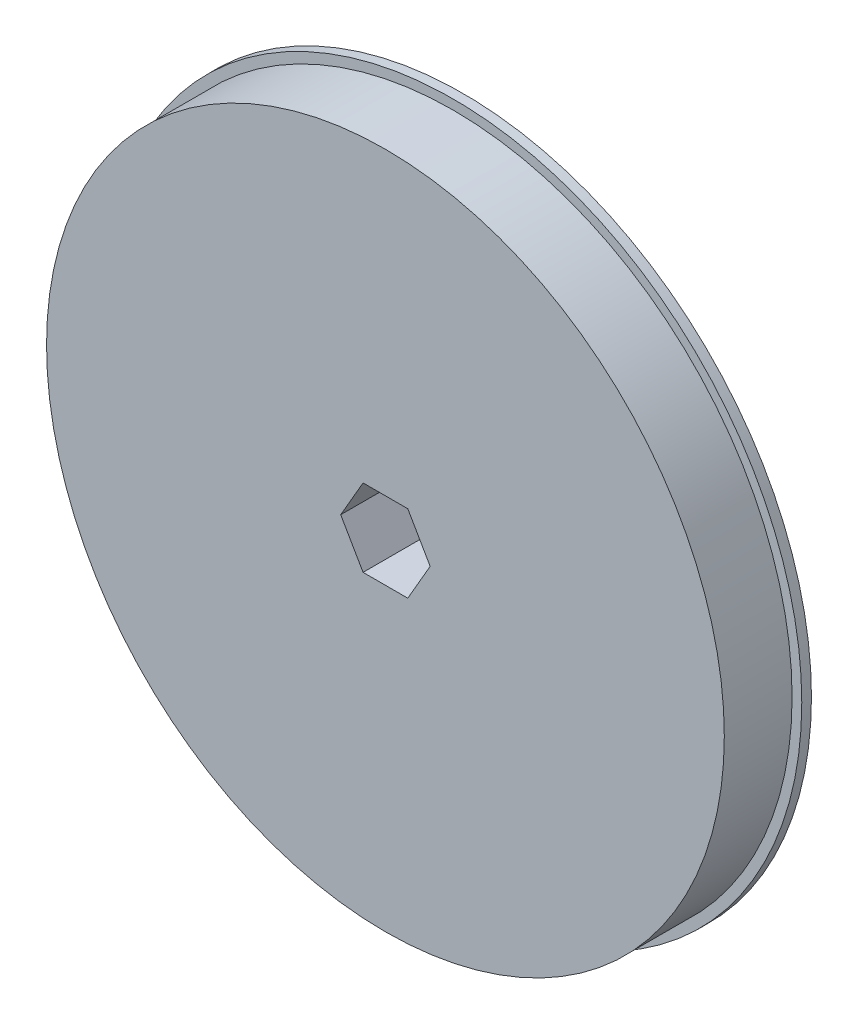
SolidWorks part; units mm, degrees
ref_plane "Front Plane" through (0, 0, 0) normal (0, 0, 1) x (1, 0, 0)
ref_plane "Top Plane" through (0, 0, 0) normal (0, 1, 0) x (1, 0, 0)
ref_plane "Right Plane" through (0, 0, 0) normal (1, 0, 0) x (0, 0, -1)
sketch "Sketch1" plane through (0, 0, 0) normal (0, 0, 1) x (1, 0, 0)
  circle A0 centre (0, 0) radius 57.15
  dimension "D1" = 114.3
extrude "Boss-Extrude1" add sketch "Sketch1" along normal blind 12.7
sketch "Sketch2" plane through (0, 0, 12.7) normal (0, 0, 1) x (1, 0, 0)
  circle A3 centre (0, 0) radius 55.5625
  circle A4 centre (0, 0) radius 57.15
  circle A5 centre (0, 0) radius 57.15
  dimension "D1" = 111.125
  dimension "D2" = 0
extrude "Cut-Extrude1" cut sketch "Sketch2" against normal blind 11.1125
sketch "Sketch3" plane through (0, 0, 0) normal (0, 0, -1) x (-1, 0, 0)
  circle A0 centre (0, 0) radius 50.8
  dimension "D1" = 101.6
extrude "Cut-Extrude2" cut sketch "Sketch3" against normal blind 9.525
sketch "Sketch4" plane through (0, 0, 9.525) normal (0, 0, -1) x (-1, 0, 0)
  circle A0 centre (0, 0) radius 12.7
  dimension "D1" = 25.4
extrude "Boss-Extrude2" add sketch "Sketch4" along normal blind 9.525
sketch "Sketch6" plane through (0, 0, 0) normal (0, 0, -1) x (-1, 0, 0)
  line L1 (7.3323, 0) -> (3.6662, 6.35)
  line L2 (3.6662, 6.35) -> (-3.6662, 6.35)
  line L3 (-3.6662, 6.35) -> (-7.3323, 0)
  line L4 (-7.3323, 0) -> (-3.6662, -6.35)
  line L5 (-3.6662, -6.35) -> (3.6662, -6.35)
  line L6 (3.6662, -6.35) -> (7.3323, 0)
  circle A0 centre (0, 0) radius 6.35 construction
  dimension "D1" = 12.7
extrude "Cut-Extrude4" cut sketch "Sketch6" against normal blind 12.7
chamfer "Chamfer1" distance 0.7937 angle 45 1 edges at (-12.7, 0, 0)
